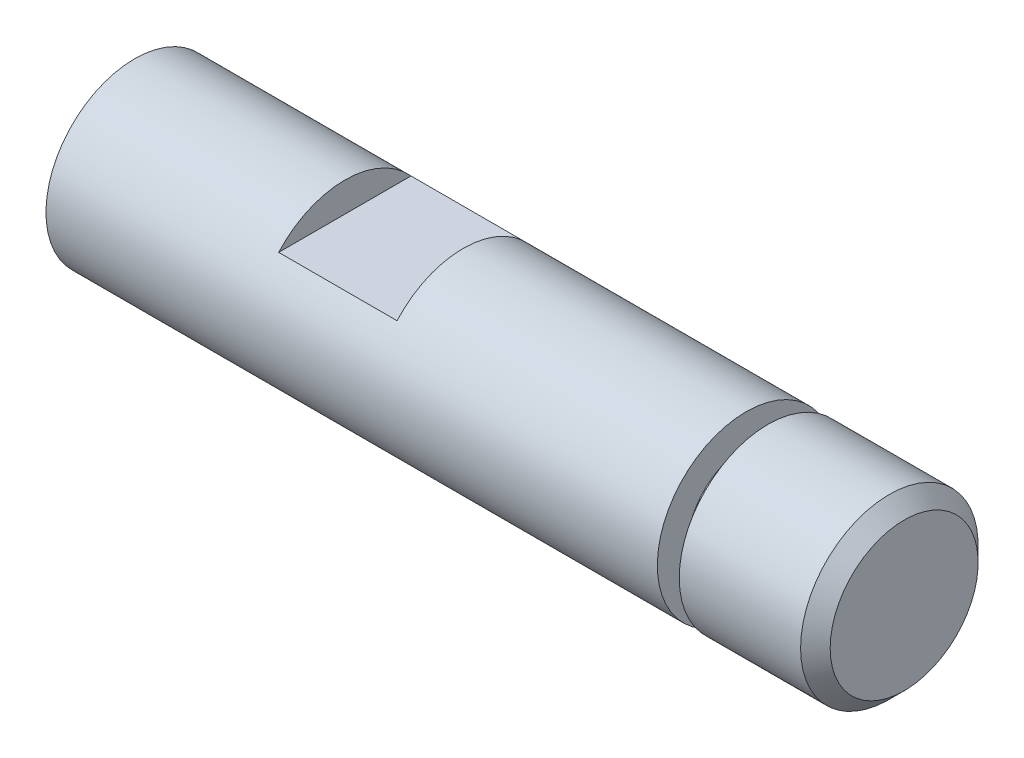
SolidWorks part; units mm, degrees
ref_plane "Plan de face" through (0, 0, 0) normal (0, 0, 1) x (1, 0, 0)
ref_plane "Plan de dessus" through (0, 0, 0) normal (0, 1, 0) x (1, 0, 0)
ref_plane "Plan de droite" through (0, 0, 0) normal (1, 0, 0) x (0, 0, -1)
sketch "Esquisse1" plane through (0, 0, 0) normal (0, 0, 1) x (1, 0, 0)
  line L0 (0, 0) -> (12.8037, 0) construction
  line L1 (0, 0) -> (0, 15.5366) construction
  line L2 (-26, 0) -> (26, 0)
  line L4 (-26, 0) -> (-26, 3)
  line L5 (-26, 3) -> (26, 3)
  line L6 (26, 0) -> (26, 3)
  point P4 (0, 0)
  dimension "D1" = 52
  dimension "D2" = 3
  dimension "D3" = 26
revolve "Révolution1" add sketch "Esquisse1" angle 360 about L0
chamfer "Chanfrein1" distance 0.5 angle 45 1 edges at (26, 0, 3)
sketch "Esquisse2" plane through (0, 0, 0) normal (0, 0, 1) x (1, 0, 0)
  line L0 (25.5, 3) -> (-26, 3) construction
  line L1 (25.5, 3) -> (-26, 3)
  line L3 (7.1, 4) -> (11.1, 4)
  line L4 (7.1, 4) -> (7.1, 2)
  line L5 (7.1, 2) -> (11.1, 2)
  line L6 (11.1, 4) -> (11.1, 2)
  line L7 (7.1, 4) -> (11.1, 2) construction
  line L8 (7.1, 2) -> (11.1, 4) construction
  point P2 (9.1, 3)
  dimension "D1" = 1
  dimension "D2" = 9.1
  dimension "D3" = 4
extrude "Enlèv. mat.-Extru.1" cut sketch "Esquisse2" against normal through all both and the other way through all contours L5 L6 L3 L4
sketch "Esquisse3" plane through (0, 0, 0) normal (0, 0, 1) x (1, 0, 0)
  line L2 (7.1, 3) -> (-26, 3) construction
  line L3 (-21.4, 3) -> (-20.66, 3)
  line L4 (0, 0) -> (0, 10.3249) construction
  line L5 (-21.4, 3) -> (-21.4, 2)
  line L6 (-21.4, 2) -> (-20.66, 2)
  line L7 (-20.66, 3) -> (-20.66, 2)
  line L8 (20.66, 3) -> (20.66, 2)
  line L9 (21.4, 2) -> (20.66, 2)
  line L10 (21.4, 3) -> (21.4, 2)
  line L11 (21.4, 3) -> (20.66, 3)
  line L17 (0, 0) -> (-35.8372, 0) construction
  dimension "D1" = 0.74
  dimension "D2" = 2
  dimension "D3" = 42.8
revolve "Enlèvement de matière-Révolution1" cut sketch "Esquisse3" angle 360 about L17
sketch "Esquisse4" plane through (-26, 0, 0) normal (-1, 0, 0) x (0, 0, 1)
  circle A1 centre (0, 0) radius 3
  circle A2 centre (0, 0) radius 3
  dimension "D1" = 0
extrude "Boss.-Extru.1" add sketch "Esquisse4" along normal blind 15
sketch "Esquisse5" plane through (0, 0, 0) normal (0, 0, 1) x (1, 0, 0)
  line L0 (11.1, 2) -> (7.1, 2) construction
  line L1 (-41, 3) -> (-29, 3)
  line L2 (-41, 3) -> (-41, 2)
  line L3 (-41, 2) -> (-29, 2)
  line L4 (-29, 3) -> (-29, 2)
  dimension "D1" = 12
extrude "Enlèv. mat.-Extru.2" cut sketch "Esquisse5" against normal through all both and the other way through all
sketch "Esquisse6" plane through (0, 0, 0) normal (0, 0, 1) x (1, 0, 0)
  line L1 (-50.2113, 11.2061) -> (0, 11.2061)
  line L2 (-50.2113, 11.2061) -> (-50.2113, -9.0114)
  line L3 (-50.2113, -9.0114) -> (0, -9.0114)
  line L4 (0, 11.2061) -> (0, -9.0114)
  dimension "D1" = 0
extrude "Enlèv. mat.-Extru.3" cut sketch "Esquisse6" against normal through all both and the other way through all
